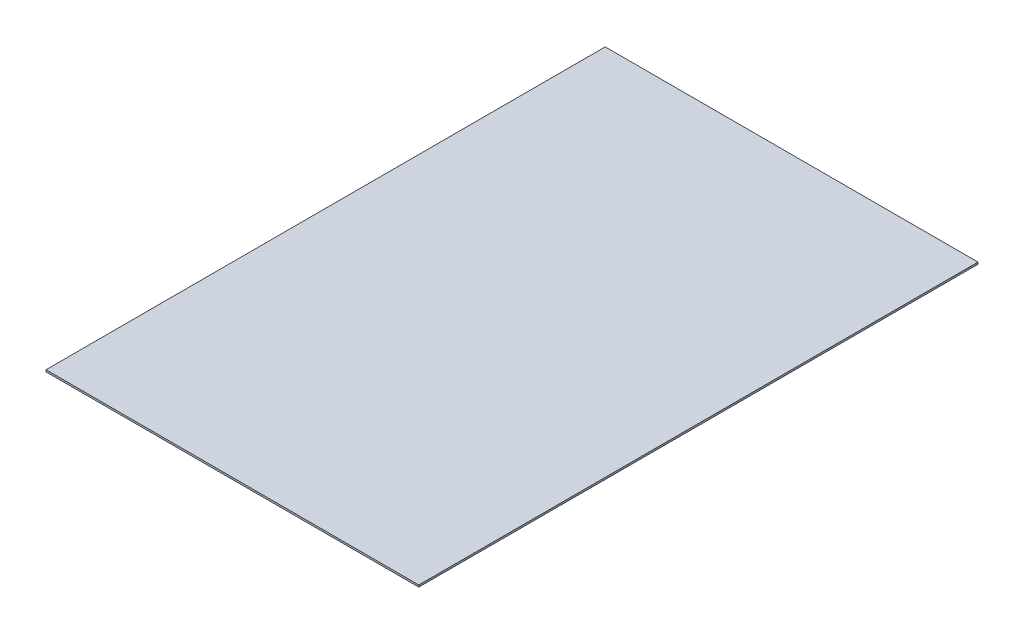
SolidWorks part; units mm, degrees
ref_plane "Front" through (0, 0, 0) normal (0, 0, 1) x (1, 0, 0)
ref_plane "Top" through (0, 0, 0) normal (0, 1, 0) x (1, 0, 0)
ref_plane "Right" through (0, 0, 0) normal (1, 0, 0) x (0, 0, -1)
sketch "Sketch1" plane through (0, 0, 0) normal (0, 1, 0) x (1, 0, 0)
  line L1 (-100, -150) -> (100, -150)
  line L2 (-100, -150) -> (-100, 150)
  line L3 (-100, 150) -> (100, 150)
  line L4 (100, -150) -> (100, 150)
  line L5 (-100, -150) -> (100, 150) construction
  line L6 (-100, 150) -> (100, -150) construction
  point P0 (0, 0)
  dimension "D1" = 300
  dimension "200" = 200
extrude "Boss-Extrude1" add sketch "Sketch1" along normal blind 1
